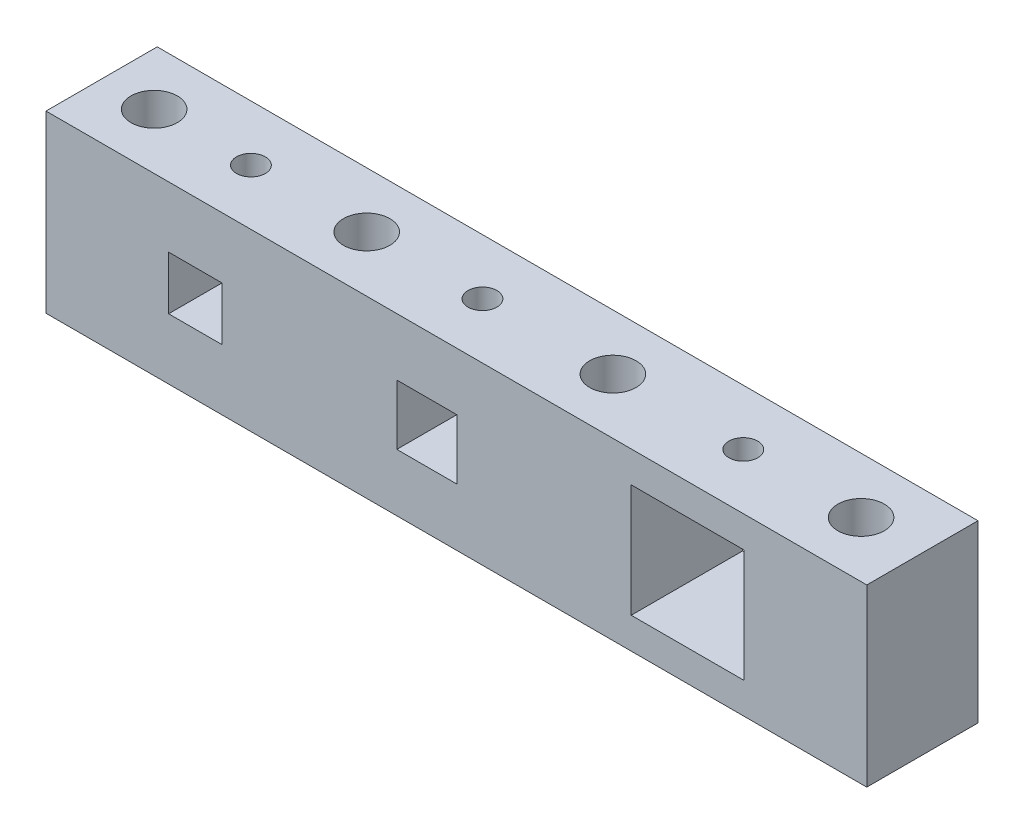
SolidWorks part; units mm, degrees
material "ABS"
ref_plane "Front Plane" through (0, 0, 0) normal (0, 0, 1) x (1, 0, 0)
ref_plane "Top Plane" through (0, 0, 0) normal (0, 1, 0) x (1, 0, 0)
ref_plane "Right Plane" through (0, 0, 0) normal (1, 0, 0) x (0, 0, -1)
sketch "Sketch1" plane through (0, 0, 0) normal (0, 0, 1) x (1, 0, 0)
  line L5 (-43.489, 10) -> (50.239, 10)
  line L6 (-43.489, 10) -> (-43.489, -10)
  line L7 (-43.489, -10) -> (50.239, -10)
  line L8 (50.239, 10) -> (50.239, -10)
  line L9 (-29.489, -3.05) -> (-23.389, -3.05)
  line L10 (-29.489, -3.05) -> (-29.489, 3.05)
  line L11 (-29.489, 3.05) -> (-23.389, 3.05)
  line L12 (-23.389, -3.05) -> (-23.389, 3.05)
  line L13 (-29.489, -3.05) -> (-23.389, 3.05) construction
  line L14 (-29.489, 3.05) -> (-23.389, -3.05) construction
  line L15 (-3.429, -3.429) -> (3.429, -3.429)
  line L16 (-3.429, -3.429) -> (-3.429, 3.429)
  line L17 (-3.429, 3.429) -> (3.429, 3.429)
  line L18 (3.429, -3.429) -> (3.429, 3.429)
  line L19 (-3.429, -3.429) -> (3.429, 3.429) construction
  line L20 (-3.429, 3.429) -> (3.429, -3.429) construction
  line L21 (23.339, -6.45) -> (36.239, -6.45)
  line L22 (23.339, -6.45) -> (23.339, 6.45)
  line L23 (23.339, 6.45) -> (36.239, 6.45)
  line L24 (36.239, -6.45) -> (36.239, 6.45)
  line L25 (23.339, -6.45) -> (36.239, 6.45) construction
  line L26 (23.339, 6.45) -> (36.239, -6.45) construction
  point P6 (-43.489, 0)
  point P8 (-26.439, 0)
  point P13 (0, 0)
  point P18 (29.789, 0)
  dimension "D1" = 12.9
  dimension "D2" = 6.858
  dimension "D3" = 6.1
  dimension "D4" = 14
  dimension "D5" = 26.439
  dimension "D6" = 29.789
  dimension "D7" = 14
  dimension "D8" = 20
extrude "Boss-Extrude1" add sketch "Sketch1" along normal blind 12.7
sketch "Sketch2" plane through (0, 10, 0) normal (0, 1, 0) x (1, 0, 0)
  line L0 (-26.439, -6.35) -> (0, -6.35) construction
  line L1 (-43.489, 0) -> (50.239, 0)
  line L2 (-43.489, 0) -> (-43.489, -12.7)
  line L3 (-43.489, -12.7) -> (50.239, -12.7)
  line L4 (50.239, 0) -> (50.239, -12.7)
  line L5 (0, -6.35) -> (29.789, -6.35) construction
  circle A0 centre (0, -6.35) radius 2 construction
  circle A1 centre (29.789, -6.35) radius 2 construction
  circle A2 centre (-26.439, -6.35) radius 2 construction
  circle A3 centre (-37.489, -6.35) radius 2.5 construction
  circle A4 centre (-13.2195, -6.35) radius 2.5 construction
  circle A5 centre (14.8945, -6.35) radius 2.5 construction
  circle A6 centre (43.239, -6.35) radius 2.5 construction
  point P6 (50.239, -6.35)
  point P22 (14.8945, -6.35)
  point P24 (-13.2195, -6.35)
  dimension "D3" = 4
  dimension "D4" = 5
  dimension "D5" = 6
  dimension "D6" = 7
  dimension "D1" = 26.439
  dimension "D2" = 29.789
hole_wizard "Tap Drill for M4x0.7 Tap1" positions "3DSketch1" profile "Sketch3" hole size "M4x0.7" standard "ANSI Metric" end condition up to next
sketch3d "3DSketch1"
  point P0 (-26.439, 10, 6.35)
  point P2 (0, 10, 6.35)
  point P4 (29.789, 10, 6.35)
sketch "Sketch3" plane through (-26.439, 10, 6.35) normal (1, 0, 0) x (0, 0, 1)
  line L0 (0, 0) -> (0, 6.95)
  line L1 (0, 6.95) -> (1.65, 6.95)
  line L2 (1.65, 6.95) -> (1.65, 0)
  line L5 (1.65, 0) -> (0, 0)
  line L11 (0, -6.35) -> (0, 107.95) construction
  dimension "Thru Hole Dia." = 3.3
  dimension "Thru Hole Depth" = 6.95
hole_wizard "M5 Clearance Hole1" positions "3DSketch2" profile "Sketch4" hole size "M5" standard "ANSI Metric" end condition up to next
sketch3d "3DSketch2"
  point P0 (-37.489, 10, 6.35)
  point P2 (-13.2195, 10, 6.35)
  point P4 (14.8945, 10, 6.35)
  point P6 (43.239, 10, 6.35)
sketch "Sketch4" plane through (-37.489, 10, 6.35) normal (1, 0, 0) x (0, 0, 1)
  line L0 (0, 0) -> (0, 20)
  line L1 (0, 20) -> (2.65, 20)
  line L2 (2.65, 20) -> (2.65, 0)
  line L5 (2.65, 0) -> (0, 0)
  line L11 (0, -6.35) -> (0, 107.95) construction
  dimension "Thru Hole Dia." = 5.3
  dimension "Thru Hole Depth" = 20
